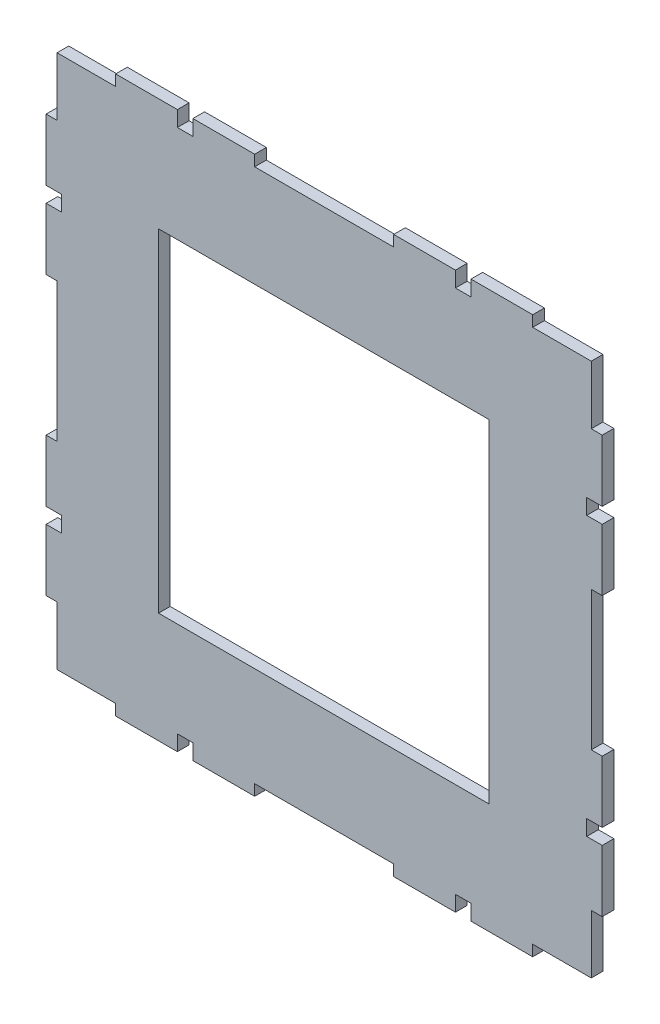
SolidWorks part; units mm, degrees
ref_plane "Front Plane" through (0, 0, 0) normal (0, 0, 1) x (1, 0, 0)
ref_plane "Top Plane" through (0, 0, 0) normal (0, 1, 0) x (1, 0, 0)
ref_plane "Right Plane" through (0, 0, 0) normal (1, 0, 0) x (0, 0, -1)
sketch "Sketch1" plane through (0, 0, 0) normal (0, 0, 1) x (1, 0, 0)
  line L4 (339.4009, 123.7222) -> (339.4009, 33.0759)
  line L5 (339.4009, 33.0759) -> (429.374, 33.0759)
  line L6 (429.374, 123.7222) -> (429.374, 33.0759)
  line L7 (339.4009, 123.7222) -> (429.374, 123.7222)
  line L236 (311.7757, 151.4169) -> (311.7757, 135.4704)
  line L237 (311.7757, 135.4704) -> (308.795, 135.4704)
  line L238 (308.795, 135.4704) -> (308.795, 118.6546)
  line L239 (308.795, 118.6546) -> (313.0176, 118.6546)
  line L240 (313.0176, 118.6546) -> (313.0176, 116.5433)
  line L241 (313.0176, 116.5433) -> (313.0176, 114.432)
  line L242 (313.0176, 114.432) -> (308.795, 114.432)
  line L243 (308.795, 114.432) -> (308.795, 97.6162)
  line L244 (308.795, 97.6162) -> (311.7757, 97.6162)
  line L245 (311.7757, 97.6162) -> (311.7757, 59.762)
  line L246 (311.7757, 59.762) -> (308.795, 59.762)
  line L247 (308.795, 59.762) -> (308.795, 42.9462)
  line L248 (308.795, 42.9462) -> (313.0176, 42.9462)
  line L249 (313.0176, 42.9462) -> (313.0176, 40.8349)
  line L250 (313.0176, 40.8349) -> (313.0176, 38.7236)
  line L251 (313.0176, 38.7236) -> (308.795, 38.7236)
  line L252 (308.795, 38.7236) -> (308.795, 21.9078)
  line L253 (308.795, 21.9078) -> (311.7757, 21.9078)
  line L254 (311.7757, 21.9078) -> (311.7757, 5.9613)
  line L255 (311.7757, 5.9613) -> (327.7221, 5.9613)
  line L256 (327.7221, 5.9613) -> (327.7221, 2.9806)
  line L257 (327.7221, 2.9806) -> (344.5379, 2.9806)
  line L258 (344.5379, 2.9806) -> (344.5379, 7.2032)
  line L259 (344.5379, 7.2032) -> (346.6492, 7.2032)
  line L260 (346.6492, 7.2032) -> (348.7605, 7.2032)
  line L261 (348.7605, 7.2032) -> (348.7605, 2.9806)
  line L262 (348.7605, 2.9806) -> (365.5763, 2.9806)
  line L263 (365.5763, 2.9806) -> (365.5763, 5.9613)
  line L264 (365.5763, 5.9613) -> (403.4305, 5.9613)
  line L265 (403.4305, 5.9613) -> (403.4305, 2.9806)
  line L266 (403.4305, 2.9806) -> (420.2464, 2.9806)
  line L267 (420.2464, 2.9806) -> (420.2464, 7.2032)
  line L268 (420.2464, 7.2032) -> (422.3576, 7.2032)
  line L269 (422.3576, 7.2032) -> (424.4689, 7.2032)
  line L270 (424.4689, 7.2032) -> (424.4689, 2.9806)
  line L271 (424.4689, 2.9806) -> (441.2848, 2.9806)
  line L272 (441.2848, 2.9806) -> (441.2848, 5.9613)
  line L273 (441.2848, 5.9613) -> (457.2312, 5.9613)
  line L274 (457.2312, 5.9613) -> (457.2312, 21.9078)
  line L275 (457.2312, 21.9078) -> (460.2119, 21.9078)
  line L276 (460.2119, 21.9078) -> (460.2119, 38.7236)
  line L277 (460.2119, 38.7236) -> (455.9893, 38.7236)
  line L278 (455.9893, 38.7236) -> (455.9893, 40.8349)
  line L279 (455.9893, 40.8349) -> (455.9893, 42.9462)
  line L280 (455.9893, 42.9462) -> (460.2119, 42.9462)
  line L281 (460.2119, 42.9462) -> (460.2119, 59.762)
  line L282 (460.2119, 59.762) -> (457.2312, 59.762)
  line L283 (457.2312, 59.762) -> (457.2312, 97.6162)
  line L284 (457.2312, 97.6162) -> (460.2119, 97.6162)
  line L285 (460.2119, 97.6162) -> (460.2119, 114.432)
  line L286 (460.2119, 114.432) -> (455.9893, 114.432)
  line L287 (455.9893, 114.432) -> (455.9893, 116.5433)
  line L288 (455.9893, 116.5433) -> (455.9893, 118.6546)
  line L289 (455.9893, 118.6546) -> (460.2119, 118.6546)
  line L290 (460.2119, 118.6546) -> (460.2119, 135.4704)
  line L291 (460.2119, 135.4704) -> (457.2312, 135.4704)
  line L292 (457.2312, 135.4704) -> (457.2312, 151.4169)
  line L293 (457.2312, 151.4169) -> (441.2848, 151.4169)
  line L294 (441.2848, 151.4169) -> (441.2848, 154.3975)
  line L295 (441.2848, 154.3975) -> (424.4689, 154.3975)
  line L296 (424.4689, 154.3975) -> (424.4689, 150.1749)
  line L297 (424.4689, 150.1749) -> (422.3576, 150.1749)
  line L298 (422.3576, 150.1749) -> (420.2464, 150.1749)
  line L299 (420.2464, 150.1749) -> (420.2464, 154.3975)
  line L300 (420.2464, 154.3975) -> (403.4305, 154.3975)
  line L301 (403.4305, 154.3975) -> (403.4305, 151.4169)
  line L302 (403.4305, 151.4169) -> (365.5763, 151.4169)
  line L303 (365.5763, 151.4169) -> (365.5763, 154.3975)
  line L304 (365.5763, 154.3975) -> (348.7605, 154.3975)
  line L305 (348.7605, 154.3975) -> (348.7605, 150.1749)
  line L306 (348.7605, 150.1749) -> (346.6492, 150.1749)
  line L307 (346.6492, 150.1749) -> (344.5379, 150.1749)
  line L308 (344.5379, 150.1749) -> (344.5379, 154.3975)
  line L309 (344.5379, 154.3975) -> (327.7221, 154.3975)
  line L310 (327.7221, 154.3975) -> (327.7221, 151.4169)
  line L311 (327.7221, 151.4169) -> (311.7757, 151.4169)
  line L630 (311.7757, 78.6891) -> (457.2312, 78.6891) construction
  line L635 (384.5034, 151.4169) -> (384.5034, 5.9613) construction
  point P0 (0, 0)
  point P693 (384.5034, 78.6891)
extrude "Boss-Extrude1" add sketch "Sketch1" along normal blind 3.175
